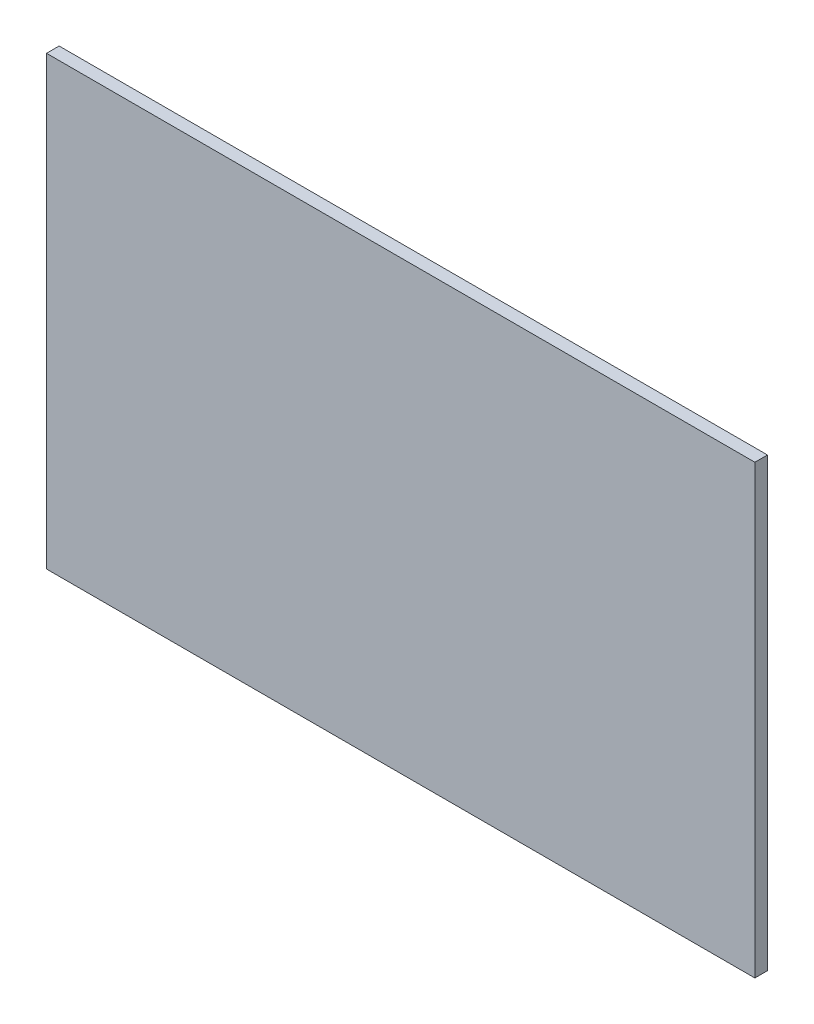
SolidWorks part; units mm, degrees
ref_plane "Front Plane" through (0, 0, 0) normal (0, 0, 1) x (1, 0, 0)
ref_plane "Top Plane" through (0, 0, 0) normal (0, 1, 0) x (1, 0, 0)
ref_plane "Right Plane" through (0, 0, 0) normal (1, 0, 0) x (0, 0, -1)
sketch "Sketch1" plane through (0, 0, 0) normal (0, 0, 1) x (1, 0, 0)
  line L1 (67.4, 42.5) -> (-67.4, 42.5)
  line L2 (67.4, 42.5) -> (67.4, -42.5)
  line L3 (67.4, -42.5) -> (-67.4, -42.5)
  line L4 (-67.4, 42.5) -> (-67.4, -42.5)
  line L5 (67.4, 42.5) -> (-67.4, -42.5) construction
  line L6 (67.4, -42.5) -> (-67.4, 42.5) construction
  point P1 (0, 0)
extrude "Boss-Extrude1" add sketch "Sketch1" along normal blind 2.4
